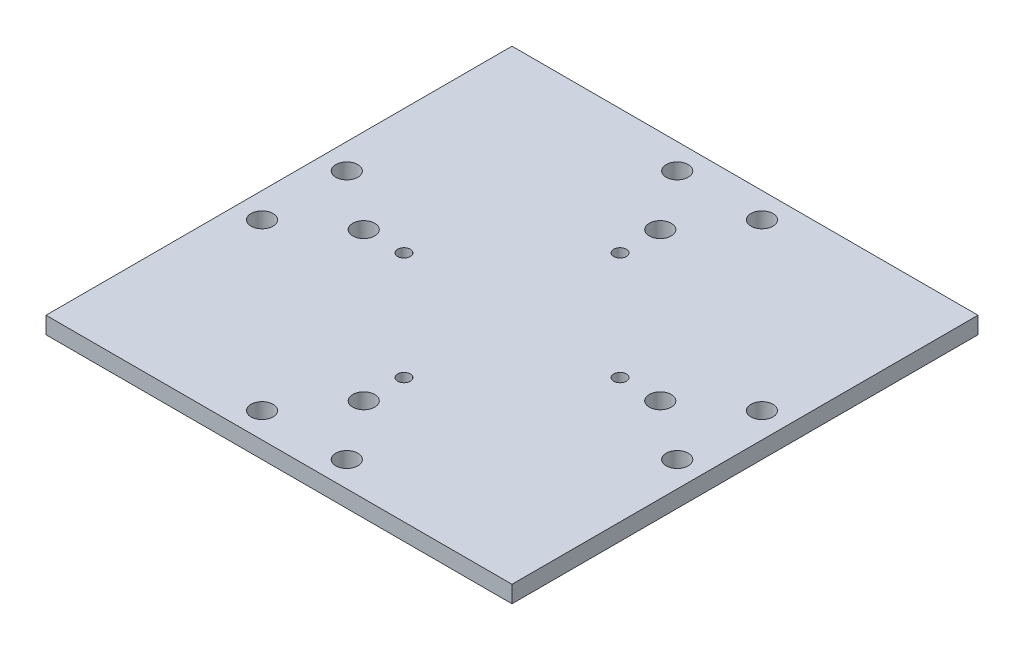
SolidWorks part; units mm, degrees
ref_plane "前视基准面" through (0, 0, 0) normal (0, 0, 1) x (1, 0, 0)
ref_plane "上视基准面" through (0, 0, 0) normal (0, 1, 0) x (1, 0, 0)
ref_plane "右视基准面" through (0, 0, 0) normal (1, 0, 0) x (0, 0, -1)
other "Configuration Table"
sketch "草图1" plane through (0, 0, 0) normal (0, 1, 0) x (1, 0, 0)
  line L1 (55, 55) -> (-55, 55)
  line L2 (-55, 55) -> (-55, -55)
  line L3 (-55, -55) -> (55, -55)
  line L4 (55, -55) -> (55, 55)
  circle A0 centre (0, 0) radius 55 construction
  dimension "D1" = 110
extrude "凸台-拉伸1" add sketch "草图1" along normal blind 4
sketch "草图2" plane through (0, 0, 0) normal (0, 1, 0) x (1, 0, 0)
  line L0 (0, 0) -> (0, 35) construction
  line L1 (0, 0) -> (-35, 0) construction
  circle A0 centre (0, 0) radius 35 construction
  circle A1 centre (0, 35) radius 2.6
  circle A2 centre (35, 0) radius 2.6
  circle A3 centre (0, -35) radius 2.6
  circle A4 centre (-35, 0) radius 2.6
  point P15 (0, 0)
  dimension "D1" = 70
  dimension "D2" = 5.2
  dimension "D3" = 90
  dimension "D4" = 4
extrude "切除-拉伸1" cut sketch "草图2" along normal through all
sketch "草图3" plane through (0, 4, 0) normal (0, 1, 0) x (1, 0, 0)
  circle A0 centre (0, 0) radius 25.5 construction
  circle A1 centre (0, 25.5) radius 1.5
  circle A2 centre (25.5, 0) radius 1.5
  circle A3 centre (0, -25.5) radius 1.5
  circle A4 centre (-25.5, 0) radius 1.5
  point P14 (0, 0)
  dimension "D1" = 51
  dimension "D2" = 3
  dimension "D3" = 4
extrude "切除-拉伸2" cut sketch "草图3" against normal through all
sketch "草图4" plane through (0, 4, 0) normal (0, 1, 0) x (1, 0, 0)
  line L0 (0, 0) -> (0, 55) construction
  line L1 (55, 55) -> (-55, 55) construction
  line L2 (-10, 49) -> (10, 49) construction
  line L3 (49, 10) -> (49, -10) construction
  line L4 (10, -49) -> (-10, -49) construction
  line L5 (-49, -10) -> (-49, 10) construction
  circle A0 centre (-10, 49) radius 2.6
  circle A1 centre (10, 49) radius 2.6
  circle A2 centre (49, 10) radius 2.6
  circle A3 centre (49, -10) radius 2.6
  circle A4 centre (10, -49) radius 2.6
  circle A5 centre (-10, -49) radius 2.6
  circle A6 centre (-49, -10) radius 2.6
  circle A7 centre (-49, 10) radius 2.6
  point P24 (0, 0)
  dimension "D2" = 5.2
  dimension "D1" = 20
  dimension "D3" = 49
  dimension "D4" = 4
extrude "切除-拉伸3" cut sketch "草图4" against normal through all
